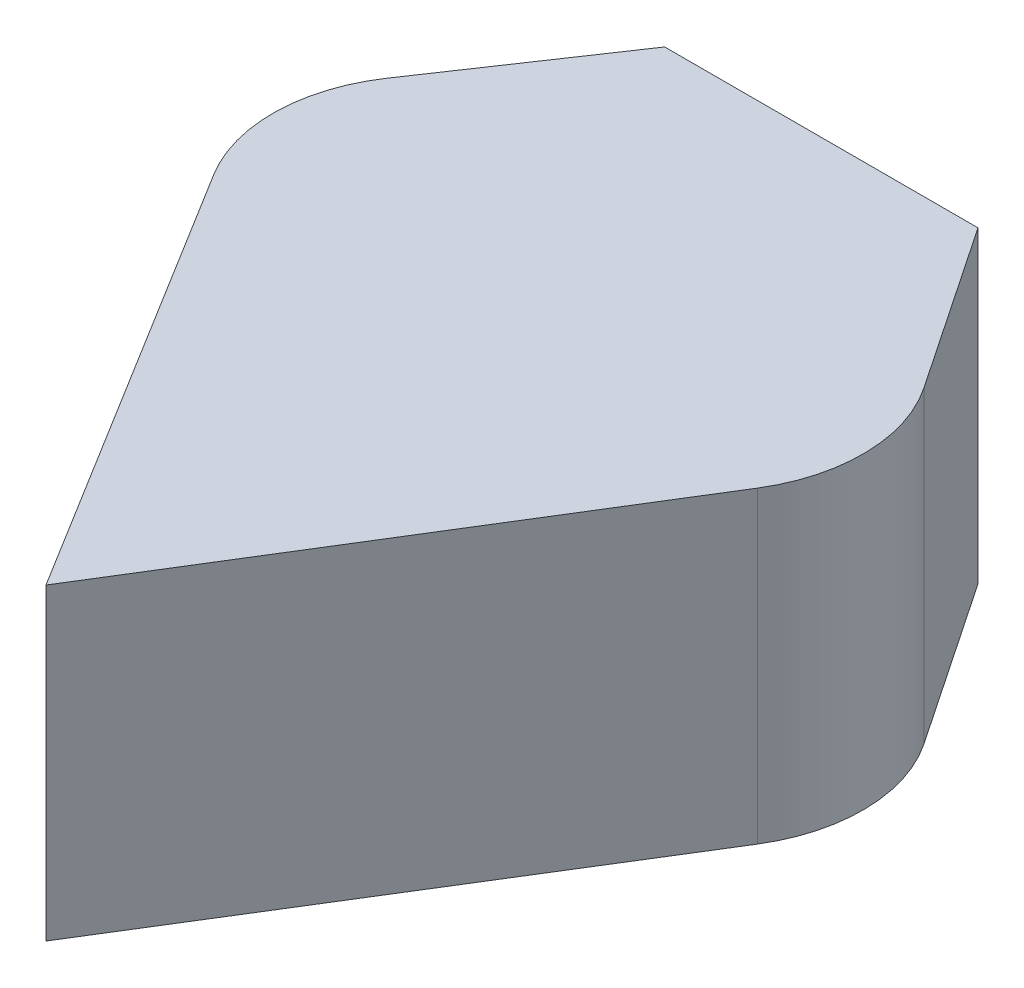
SolidWorks part; units mm, degrees
ref_plane "Front Plane" through (0, 0, 0) normal (0, 0, 1) x (1, 0, 0)
ref_plane "Top Plane" through (0, 0, 0) normal (0, 1, 0) x (1, 0, 0)
ref_plane "Right Plane" through (0, 0, 0) normal (1, 0, 0) x (0, 0, -1)
other "Graphic1" [suppressed]
other "Iron (Closed) -1" [suppressed]
other "mesh109 (Closed) -1" [suppressed]
sketch "Sketch1" plane through (0, 0, 0) normal (0, 1, 0) x (1, 0, 0)
  line L0 (1.348, -1.3126) -> (1.3734, -1.3126)
  line L1 (1.3734, -1.3126) -> (1.3824, -1.3261)
  line L2 (1.3827, -1.3399) -> (1.3607, -1.3755)
  line L3 (1.348, -1.3126) -> (1.3389, -1.3261)
  line L4 (1.3386, -1.3399) -> (1.3607, -1.3755)
  line L5 (1.3607, -1.3126) -> (1.3607, -1.3755) construction
  arc A0 (1.3389, -1.3261) -> (1.3386, -1.3399) centre (1.3495, -1.3332) ccw
  arc A1 (1.3824, -1.3261) -> (1.3827, -1.3399) centre (1.3719, -1.3332) cw
  point P17 (0, 0)
  dimension "D1" = 0.0127
  dimension "D3" = 1.3389
  dimension "D7" = 1.3126
  dimension "D2" = 1.3386
  dimension "D4" = 1.348
  dimension "D5" = 1.3495
  dimension "D6" = 1.3607
extrude "Boss-Extrude1" add sketch "Sketch1" along normal mid plane 0.025
